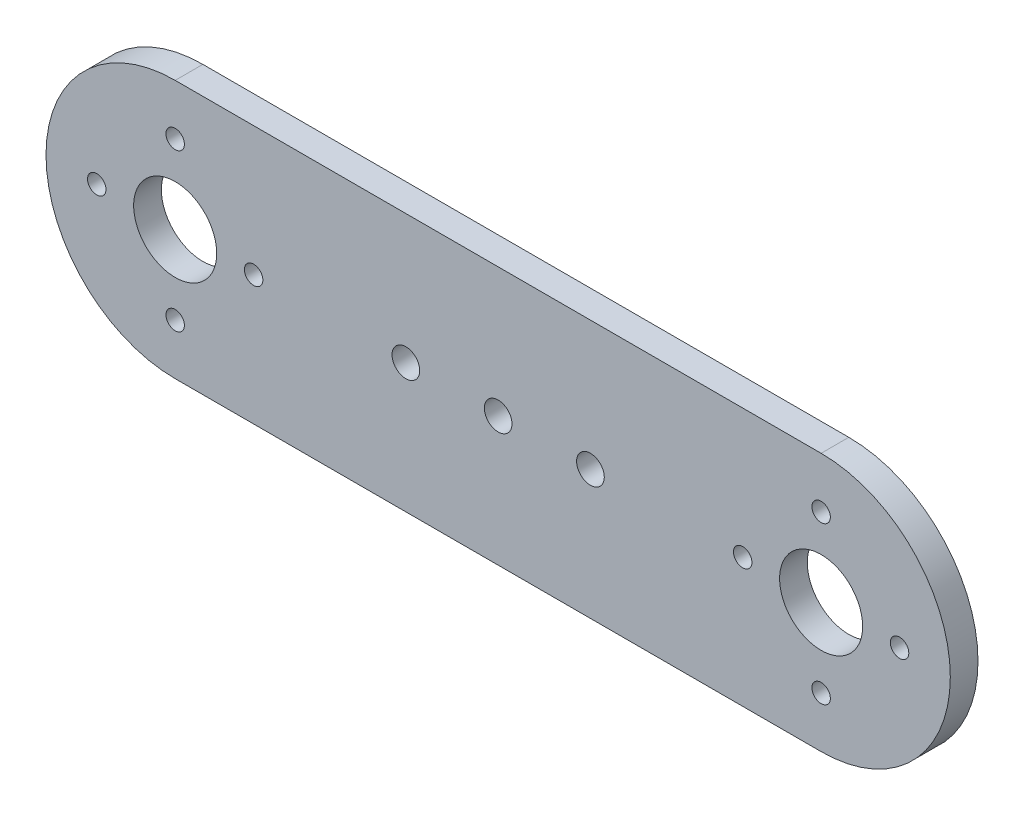
SolidWorks part; units mm, degrees
ref_plane "Front Plane" through (0, 0, 0) normal (0, 0, 1) x (1, 0, 0)
ref_plane "Top Plane" through (0, 0, 0) normal (0, 1, 0) x (1, 0, 0)
ref_plane "Right Plane" through (0, 0, 0) normal (1, 0, 0) x (0, 0, -1)
sketch "Sketch1" plane through (0, 0, 0) normal (0, 0, 1) x (1, 0, 0)
  line L0 (0, 14) -> (70, 14)
  line L1 (0, -14) -> (70, -14)
  line L2 (-1000, 0) -> (49000, 0) construction
  line L3 (35, -1005.5483) -> (35, 48994.4517) construction
  line L4 (25, -1005.6702) -> (25, 48994.3298) construction
  line L5 (45, -1008.9616) -> (45, 48991.0384) construction
  circle A0 centre (0, 0) radius 8.5 construction
  circle A1 centre (0, 0) radius 4.5
  circle A2 centre (0, 8.5) radius 1
  circle A3 centre (8.5, 0) radius 1
  circle A4 centre (0, -8.5) radius 1
  circle A5 centre (-8.5, 0) radius 1
  circle A6 centre (70, 0) radius 4.5
  circle A7 centre (70, 8.5) radius 1
  circle A8 centre (78.5, 0) radius 1
  circle A9 centre (70, -8.5) radius 1
  circle A10 centre (61.5, 0) radius 1
  circle A11 centre (70, 0) radius 8.5 construction
  arc A12 (0, 14) -> (0, -14) centre (0, 0) ccw
  arc A13 (70, -14) -> (70, 14) centre (70, 0) ccw
  circle A14 centre (25, 0) radius 1.5
  circle A15 centre (35, 0) radius 1.5
  circle A16 centre (45, 0) radius 1.5
  dimension "D1" = 9
  dimension "D2" = 17
  dimension "D3" = 2
  dimension "D4" = 2
  dimension "D5" = 2
  dimension "D6" = 2
  dimension "D9" = 28
  dimension "D10" = 28
  dimension "D14" = 3
  dimension "D15" = 3
  dimension "D16" = 3
  dimension "D8" = 70
  dimension "D11" = 35
  dimension "D12" = 10
  dimension "D13" = 10
  dimension "D7" = 2
extrude "Boss-Extrude1" add sketch "Sketch1" along normal blind 3
